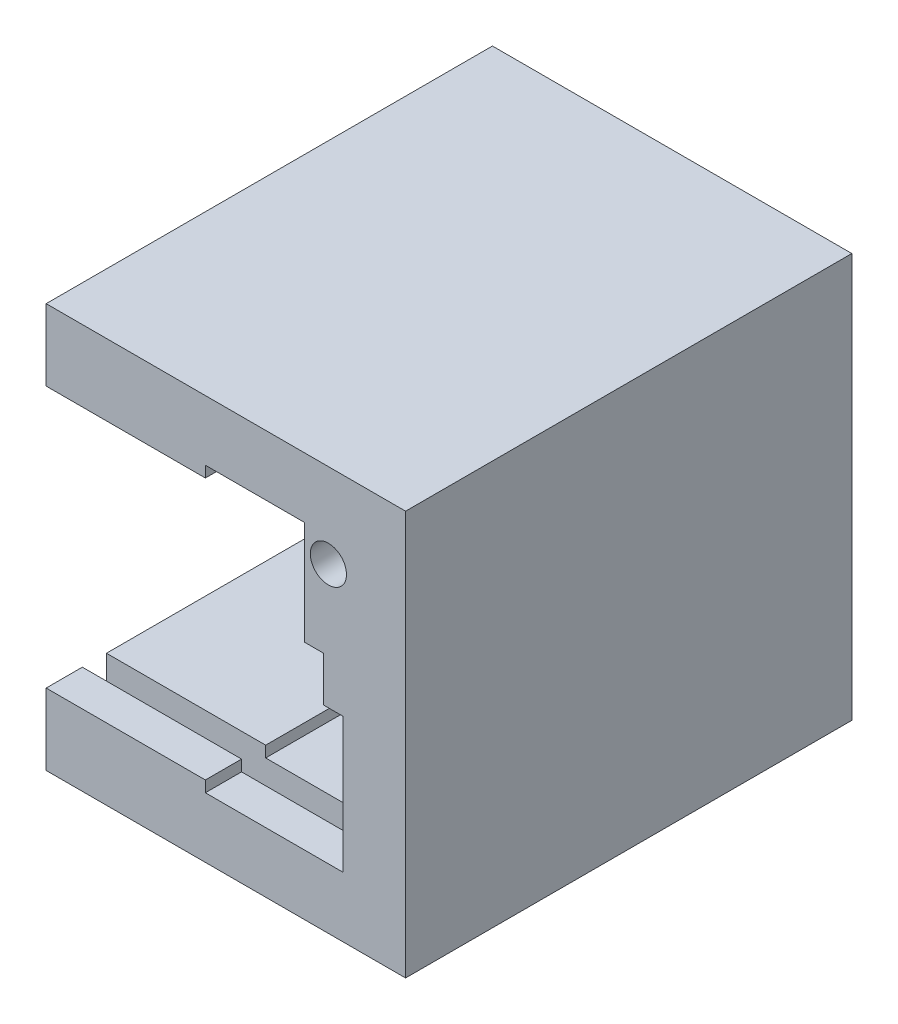
SolidWorks part; units mm, degrees
ref_plane "Front Plane" through (0, 0, 0) normal (0, 0, 1) x (1, 0, 0)
ref_plane "Top Plane" through (0, 0, 0) normal (0, 1, 0) x (1, 0, 0)
ref_plane "Right Plane" through (0, 0, 0) normal (1, 0, 0) x (0, 0, -1)
sketch "Sketch1" plane through (0, 0, 0) normal (0, 0, 1) x (1, 0, 0)
  line L0 (0, 10.6426) -> (0, -10.6426) construction
  line L1 (-9.4615, 10.6426) -> (9.4615, 10.6426)
  line L2 (-9.4615, 10.6426) -> (-9.4615, -10.6426)
  line L3 (-9.4615, -10.6426) -> (9.4615, -10.6426)
  line L4 (9.4615, 10.6426) -> (9.4615, -10.6426)
  dimension "D1" = 18.923
  dimension "D2" = 21.2852
extrude "Boss-Extrude1" add sketch "Sketch1" along normal blind 23.495 contours L1 L4 L3 L2
sketch "Sketch2" plane through (0, 0, 23.495) normal (0, 0, 1) x (1, 0, 0)
  line L0 (-9.4615, 10.6426) -> (-9.4615, -10.6426) construction
  line L1 (-9.4615, 10.6426) -> (9.4615, 10.6426) construction
  line L2 (9.4615, 10.6426) -> (9.4615, -10.6426) construction
  line L3 (-9.4615, -10.6426) -> (9.4615, -10.6426) construction
  line L4 (-9.4615, 6.8834) -> (-9.4615, -6.8834)
  line L5 (-9.4615, 10.6426) -> (9.4615, 10.6426)
  line L6 (9.4615, 10.6426) -> (9.4615, -10.6426)
  line L7 (-9.4615, -10.6426) -> (9.4615, -10.6426)
  line L8 (-9.4615, 6.8834) -> (-1.0795, 6.8834)
  line L9 (-1.0795, 6.8834) -> (-1.0795, 7.4676)
  line L10 (-1.0795, 7.4676) -> (4.1275, 7.4676)
  line L11 (5.1435, -0.3556) -> (5.1435, 2.0066)
  line L12 (-9.4615, -6.8834) -> (-1.0795, -6.8834)
  line L13 (-1.0795, -6.8834) -> (-1.0795, -7.4676)
  line L14 (-1.0795, -7.4676) -> (6.1595, -7.4676)
  line L15 (5.1435, 2.0066) -> (4.1275, 2.0066)
  line L16 (6.1595, -7.4676) -> (6.1595, -0.3556)
  line L17 (6.1595, -0.3556) -> (5.1435, -0.3556)
  line L18 (4.1275, 2.0066) -> (4.1275, 7.4676)
  dimension "D1" = 13.7668
  dimension "D2" = 3.7592
  dimension "D3" = 14.9352
  dimension "D4" = 0.5842
  dimension "D5" = 7.112
  dimension "D6" = 2.032
  dimension "D7" = 7.239
  dimension "D8" = 5.207
  dimension "D10" = 5.461
  dimension "D11" = 6.223
  dimension "D12" = 5.334
extrude "Cut-Extrude1" cut sketch "Sketch2" against normal blind 18.1102 contours L8 L9 L10 L18 L15 L11 L17 L16 L14 L13 L12 L4
sketch "Sketch3" plane through (0, 0, 5.3848) normal (0, 0, 1) x (1, 0, 0)
  line L0 (-1.0795, 7.4676) -> (4.1275, 7.4676) construction
  line L1 (-1.0795, 2.0066) -> (5.1435, 2.0066)
  line L2 (-1.0795, 2.0066) -> (-1.0795, -2.0066)
  line L3 (-1.0795, -2.0066) -> (5.1435, -2.0066)
  line L4 (5.1435, 2.0066) -> (5.1435, -2.0066)
  line L5 (-1.0795, 6.8834) -> (-1.0795, 7.4676) construction
  dimension "D1" = 6.223
  dimension "D2" = 4.0132
  dimension "D3" = 5.461
  dimension "D4" = 0
extrude "Cut-Extrude2" cut sketch "Sketch3" against normal blind 3.4798 contours L1 L4 L3 L2
sketch "Sketch4" plane through (0, 0, 5.3848) normal (0, 0, 1) x (1, 0, 0)
  line L0 (6.1595, -7.4676) -> (6.1595, -0.3556) construction
  line L1 (6.1595, -7.4676) -> (3.1877, -7.4676)
  line L2 (6.1595, -7.4676) -> (6.1595, -1.8034)
  line L3 (6.1595, -1.8034) -> (3.1877, -1.8034)
  line L4 (3.1877, -7.4676) -> (3.1877, -1.8034)
  line L5 (-1.0795, -7.4676) -> (6.1595, -7.4676) construction
  dimension "D1" = 2.9718
  dimension "D2" = 5.6642
  dimension "D3" = 0
extrude "Cut-Extrude3" cut sketch "Sketch4" against normal blind 1.4478
sketch "Sketch5" plane through (-9.4615, 0, 0) normal (-1, 0, 0) x (0, 0, 1)
  line L0 (23.495, 10.6426) -> (0, 10.6426) construction
  line L1 (20.32, 8.7376) -> (21.59, 8.7376)
  line L2 (20.32, 8.7376) -> (20.32, -8.7376)
  line L3 (20.32, -8.7376) -> (21.59, -8.7376)
  line L4 (21.59, 8.7376) -> (21.59, -8.7376)
  line L5 (23.495, -10.6426) -> (0, -10.6426) construction
  line L6 (5.3848, 6.8834) -> (5.3848, -6.8834) construction
  dimension "D1" = 1.905
  dimension "D2" = 1.905
  dimension "D3" = 1.27
  dimension "D4" = 14.9352
extrude "Cut-Extrude4" cut sketch "Sketch5" against normal blind 16.51
sketch "Sketch7" plane through (0, 0, 23.495) normal (0, 0, 1) x (1, 0, 0)
  line L0 (-1.0795, 7.4676) -> (4.1275, 7.4676) construction
  line L1 (4.1275, 2.0066) -> (4.1275, 7.4676) construction
  circle A0 centre (5.3975, 6.1976) radius 0.9525
  dimension "D3" = 1.905
  dimension "D1" = 1.27
  dimension "D2" = 1.27
extrude "Cut-Extrude6" cut sketch "Sketch7" against normal blind 5.08 contours A0
